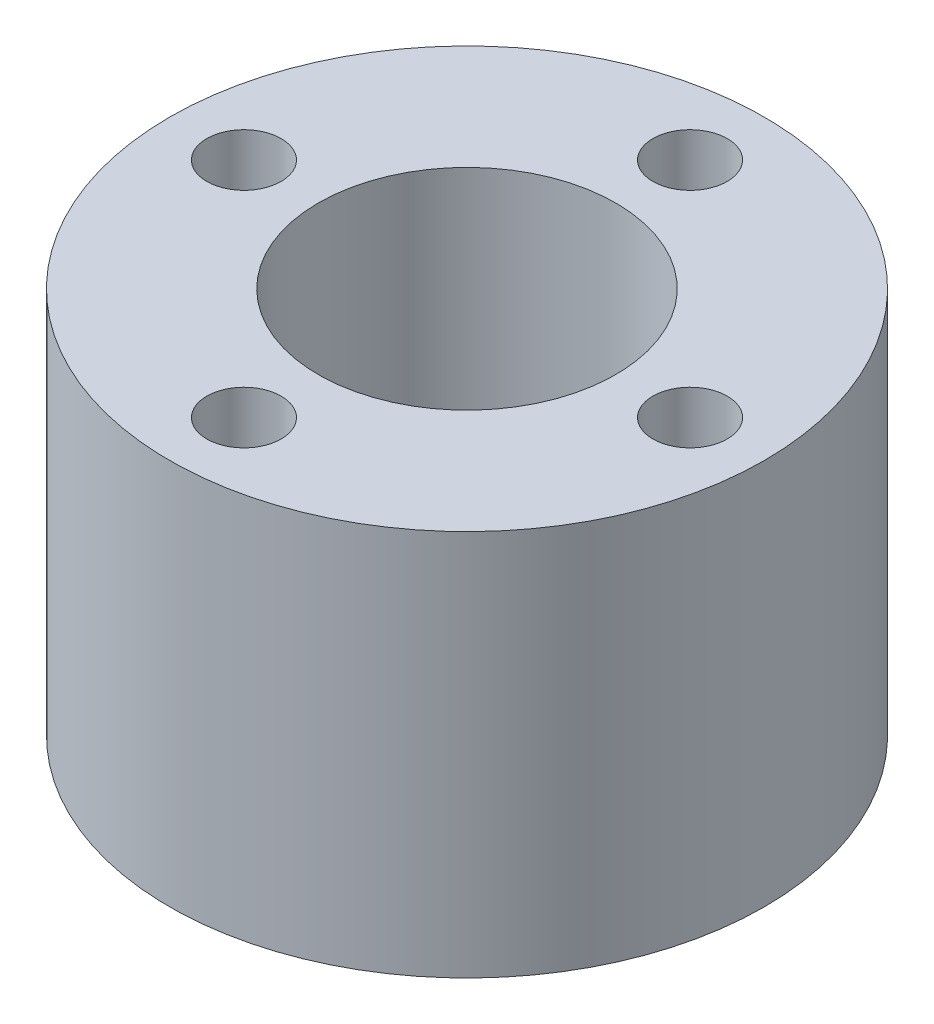
SolidWorks part; units mm, degrees
material "合金钢"
ref_plane "前视基准面" through (0, 0, 0) normal (0, 0, 1) x (1, 0, 0)
ref_plane "上视基准面" through (0, 0, 0) normal (0, 1, 0) x (1, 0, 0)
ref_plane "右视基准面" through (0, 0, 0) normal (1, 0, 0) x (0, 0, -1)
other "Configuration Table"
sketch "草图2" plane through (0, 0, 0) normal (0, 0, 1) x (1, 0, 0)
  line L0 (0, 13) -> (0, 0) construction
  line L6 (5, 13) -> (10, 13)
  line L7 (10, 13) -> (10, 0)
  line L8 (10, 0) -> (5, 0)
  line L9 (5, 0) -> (5, 13)
  dimension "D1" = 10
  dimension "D2" = 20
  dimension "D3" = 13
revolve "旋转1" add sketch "草图2" angle 360 about L0
sketch "草图4" plane through (0, 13, 0) normal (0, 1, 0) x (1, 0, 0)
  line L0 (0, 10) -> (0, 7.5) construction
  line L1 (0, 7.5) -> (0, 5) construction
  circle A1 centre (0, 0) radius 7.5 construction
  circle A2 centre (0, 0) radius 10 construction
  circle A3 centre (0, 0) radius 5 construction
  circle A4 centre (0, 7.5) radius 1.25
  circle A5 centre (7.5, 0) radius 1.25
  circle A6 centre (0, -7.5) radius 1.25
  circle A7 centre (-7.5, 0) radius 1.25
  point P17 (0, 0)
  dimension "D1" = 2.5
  dimension "D2" = 4
extrude "切除-拉伸1" cut sketch "草图4" against normal through all
equation "\"D\"= 10"
equation "\"D1\"= 20"
equation "\"L\"= 13"
equation "\"D1@草图2\"=\"D\""
equation "\"D2@草图2\"=\"D1\""
equation "\"D3@草图2\"=\"L\""
equation "\"M\"= 2.5"
equation "\"N\"= 4"
equation "\"D1@草图4\"=\"M\""
equation "\"D2@草图4\"=\"N\""
